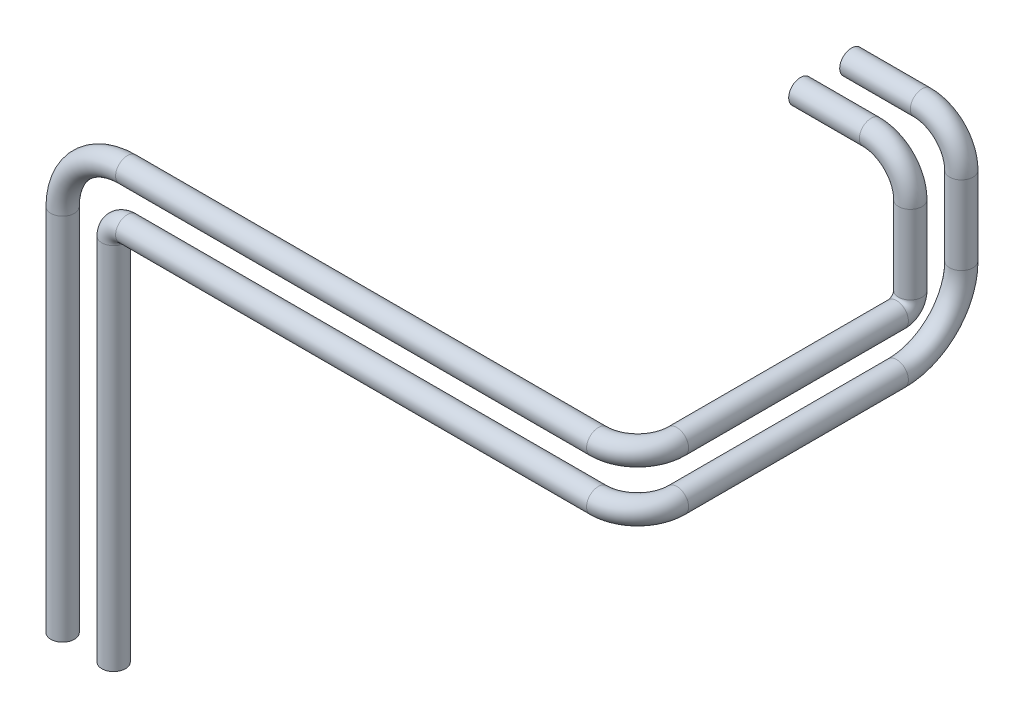
SolidWorks part; units mm, degrees
ref_plane "Front Plane" through (0, 0, 0) normal (0, 0, 1) x (1, 0, 0)
ref_plane "Top Plane" through (0, 0, 0) normal (0, 1, 0) x (1, 0, 0)
ref_plane "Right Plane" through (0, 0, 0) normal (1, 0, 0) x (0, 0, -1)
sketch "Sketch5" plane through (0, 0, 0) normal (0, 1, 0) x (1, 0, 0)
  line L0 (3.25, 0) -> (0, 0) construction
  line L1 (0, 0) -> (-3.25, 0) construction
  circle A0 centre (-3.25, 0) radius 1.5
  circle A1 centre (3.25, 0) radius 1.5
  dimension "D1" = 3
  dimension "D2" = 6.5
sketch3d "3DSketch1"
  line L0 (0, 0, 0) -> (0, 47, 0)
  line L1 (5, 52, 0) -> (65, 52, 0)
  line L2 (70, 52, -5) -> (70, 52, -33)
  line L3 (70, 57, -38) -> (70, 67, -38)
  line L4 (65, 72, -38) -> (56, 72, -38)
  arc A0 (0, 47, 0) -> (5, 52, 0) centre (5, 47, 0) ccw
  arc A1 (70, 52, -5) -> (65, 52, 0) centre (65, 52, -5) ccw
  arc A2 (70, 52, -33) -> (70, 57, -38) centre (70, 57, -33) ccw
  arc A3 (65, 72, -38) -> (70, 67, -38) centre (65, 67, -38) ccw
  point P9 (0, 52, 0)
  point P10 (5, 47, -5)
  point P13 (70, 52, 0)
  point P14 (65, 47, -5)
  point P17 (70, 52, -38)
  point P18 (75, 57, -33)
  point P21 (70, 72, -38)
  point P22 (65, 67, -43)
  dimension "D6" = 5
  dimension "D7" = 5
  dimension "D8" = 5
  dimension "D9" = 5
  dimension "D1" = 52
  dimension "D2" = 70
  dimension "D3" = 14
  dimension "D4" = 20
  dimension "D5" = 38
sweep "Sweep1" add profiles "Sketch5" path "3DSketch1"
other "Freeze***"
